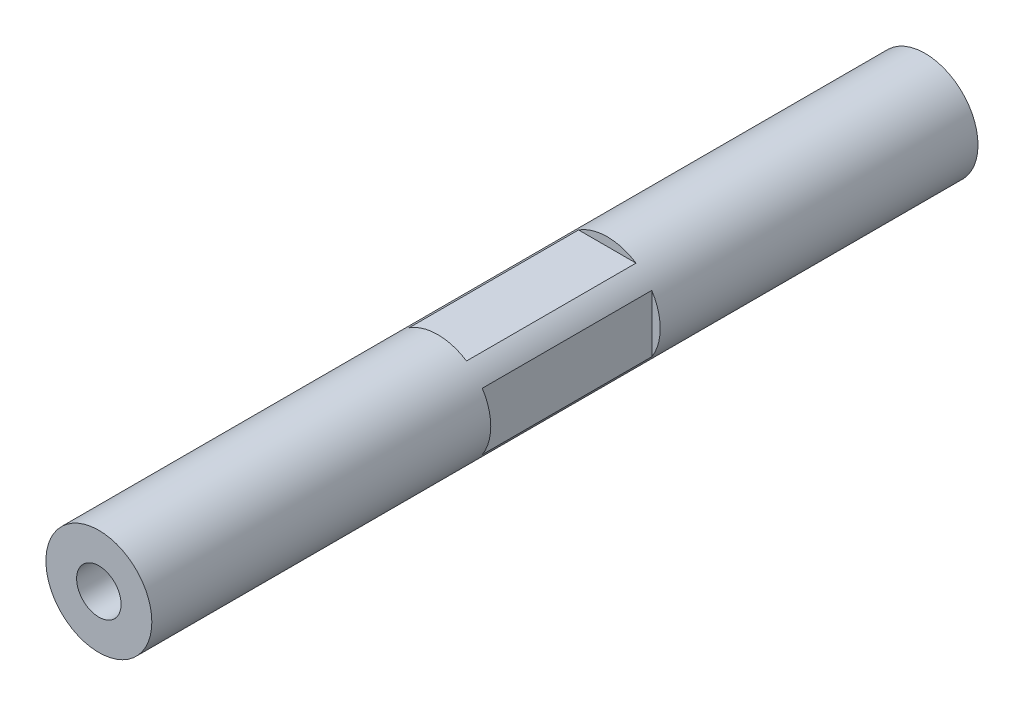
SolidWorks part; units mm, degrees
material "SKD11淬火HRC56-60"
ref_plane "前基準面" through (0, 0, 0) normal (0, 0, 1) x (1, 0, 0)
ref_plane "上基準面" through (0, 0, 0) normal (0, 1, 0) x (1, 0, 0)
ref_plane "右基準面" through (0, 0, 0) normal (1, 0, 0) x (0, 0, -1)
sketch "草图1" plane through (0, 0, 0) normal (0, 0, 1) x (1, 0, 0)
  circle A0 centre (0, 0) radius 5
  dimension "D1" = 10
extrude "凸台-拉伸1" add sketch "草图1" along normal blind 78
hole_wizard "M5 螺纹孔1" positions "草图3" profile "草图2" tap size "M5" standard "ISO"
sketch "草图3" plane through (0, 0, 78) normal (0, 0, 1) x (1, 0, 0)
  point P0 (0, 0)
sketch "草图2" plane through (0, 0, 78) normal (1, 0, 0) x (0, -1, 0)
  line L0 (0, 0) -> (0, 13.6618)
  line L1 (0, 13.6618) -> (2.1, 12.4)
  line L2 (2.1, 12.4) -> (2.1, 0)
  line L5 (2.1, 0) -> (0, 0)
  line L10 (0, 13.6618) -> (-2.1, 12.4) construction
  line L11 (0, -6.35) -> (0, 107.95) construction
  dimension "螺纹孔钻头直径" = 4.2
  dimension "螺纹孔钻头深度" = 12.4
  dimension "导头角度" = 118
cosmetic thread "孔螺蚊线1" parameters "D1"=10, "D2"=5
hole_wizard "M5 螺纹孔2" positions "草图5" profile "草图4" tap size "M5" standard "ISO"
sketch "草图5" plane through (0, 0, 0) normal (0, 0, -1) x (-1, 0, 0)
  point P0 (0, 0)
sketch "草图4" plane through (0, 0, 0) normal (1, 0, 0) x (0, 1, 0)
  line L0 (0, 0) -> (0, 13.6618)
  line L1 (0, 13.6618) -> (2.1, 12.4)
  line L2 (2.1, 12.4) -> (2.1, 0)
  line L5 (2.1, 0) -> (0, 0)
  line L10 (0, 13.6618) -> (-2.1, 12.4) construction
  line L11 (0, -6.35) -> (0, 107.95) construction
  dimension "螺纹孔钻头直径" = 4.2
  dimension "螺纹孔钻头深度" = 12.4
  dimension "导头角度" = 118
cosmetic thread "孔螺蚊线2" parameters "D1"=10, "D2"=5
ref_plane "基准面1" through (0, 0, 38) normal (0, 0, 1) x (1, 0, 0)
sketch "草图6" plane through (0, 0, 38) normal (0, 0, 1) x (1, 0, 0)
  line L0 (0, 0) -> (0, 6.759) construction
  line L1 (-11.706, 3.5458) -> (-4.2, 3.5458)
  line L2 (-11.706, 3.5458) -> (-11.706, -4.4255)
  line L3 (-11.706, -4.4255) -> (-4.2, -4.4255)
  line L4 (-4.2, 3.5458) -> (-4.2, -4.4255)
  line L5 (-3.4104, 8.6274) -> (3.4316, 8.6274)
  line L6 (-3.4104, 8.6274) -> (-3.4104, 4.2)
  line L7 (-3.4104, 4.2) -> (3.4316, 4.2)
  line L8 (3.4316, 8.6274) -> (3.4316, 4.2)
  line L9 (10.676, 3.5458) -> (4.2, 3.5458)
  line L10 (10.676, 3.5458) -> (10.676, -3.8385)
  line L11 (10.676, -3.8385) -> (4.2, -3.8385)
  line L12 (4.2, 3.5458) -> (4.2, -3.8385)
  line L13 (-3.5509, -8.8274) -> (3.4008, -8.8274)
  line L14 (-3.5509, -8.8274) -> (-3.5509, -4.2)
  line L15 (-3.5509, -4.2) -> (3.4008, -4.2)
  line L16 (3.4008, -8.8274) -> (3.4008, -4.2)
  line L17 (0, 0) -> (8.1897, 0) construction
  dimension "D1" = 8.4
  dimension "D2" = 8.4
extrude "切除-拉伸1" cut sketch "草图6" against normal blind 8 and the other way blind 8
